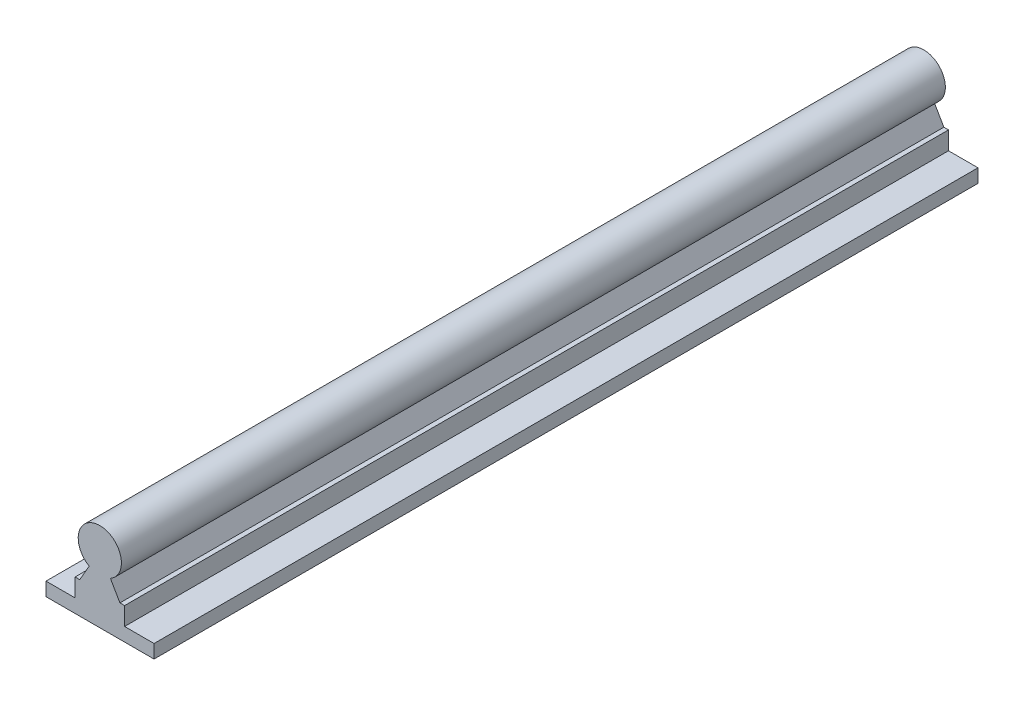
SolidWorks part; units mm, degrees
ref_plane "Plan de face" through (0, 0, 0) normal (0, 0, 1) x (1, 0, 0)
ref_plane "Plan de dessus" through (0, 0, 0) normal (0, 1, 0) x (1, 0, 0)
ref_plane "Plan de droite" through (0, 0, 0) normal (1, 0, 0) x (0, 0, -1)
sketch "Esquisse1" plane through (0, 0, 0) normal (0, 0, 1) x (1, 0, 0)
  line L0 (-25.9313, -2.761) -> (-15.1813, -2.761)
  line L1 (-15.1813, -2.761) -> (-15.1813, 3.939)
  line L2 (-15.1813, 3.939) -> (-13.4531, 3.939)
  line L3 (-13.4531, 3.939) -> (-9.9313, 10.039)
  line L5 (-2.0896, 10.039) -> (1.4322, 3.939)
  line L6 (1.4322, 3.939) -> (3.1604, 3.939)
  line L7 (3.1604, 3.939) -> (3.1604, -2.761)
  line L8 (3.1604, -2.761) -> (14.0687, -2.761)
  line L9 (14.0687, -2.761) -> (14.0687, -7.761)
  line L14 (14.0687, -7.761) -> (-25.9313, -7.761)
  line L15 (-25.9313, -7.761) -> (-25.9313, -2.761)
  line L16 (-25.9313, -2.761) -> (-25.9155, -2.8404)
  arc A1 (-9.9313, 10.039) -> (-2.0896, 10.039) centre (-6.0104, 17.0123) cw
  dimension "D1" = 8
extrude "Boss.-Extru.1" add sketch "Esquisse1" along normal blind 305 contours L0 L1 L2 L3 A1 L5 L6 L7 L8 L9 L14 L15
